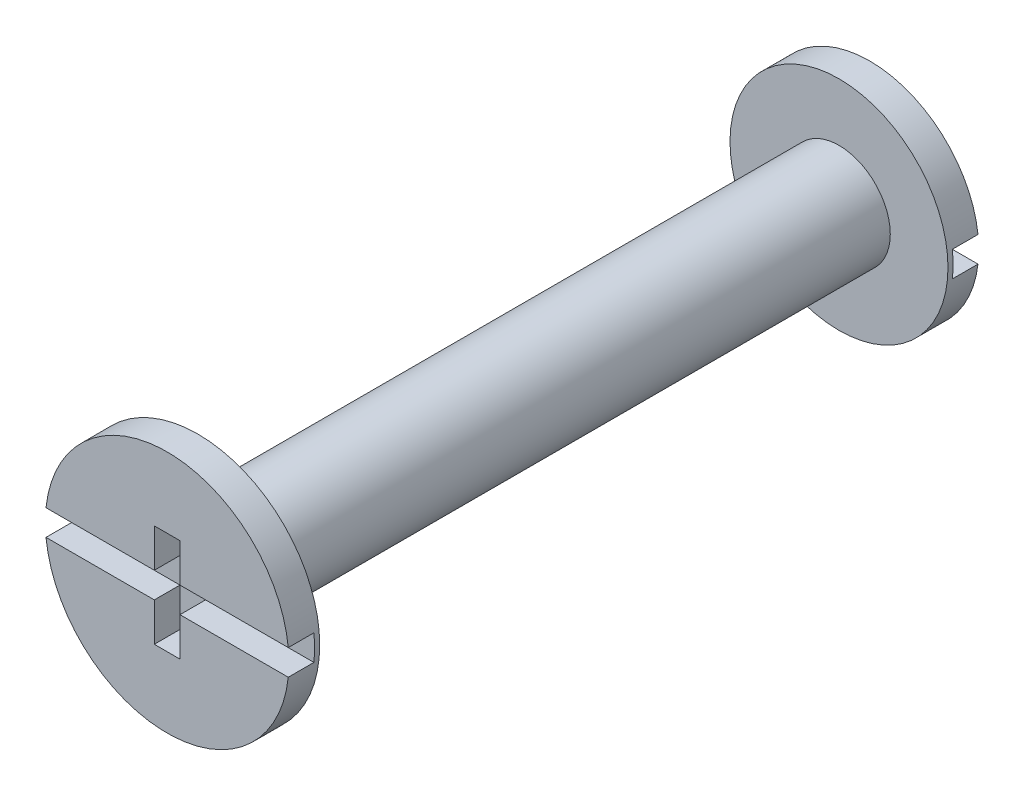
SolidWorks part; units mm, degrees
material "镀铬不锈钢"
ref_plane "前视基准面" through (0, 0, 0) normal (0, 0, 1) x (1, 0, 0)
ref_plane "上视基准面" through (0, 0, 0) normal (0, 1, 0) x (1, 0, 0)
ref_plane "右视基准面" through (0, 0, 0) normal (1, 0, 0) x (0, 0, -1)
sketch "草图1" plane through (0, 0, 0) normal (0, 0, 1) x (1, 0, 0)
  circle A0 centre (0, 0) radius 4.25
  dimension "D1" = 8.5
extrude "凸台-拉伸1" add sketch "草图1" along normal blind 1.2
sketch "草图2" plane through (0, 0, 1.2) normal (0, 0, 1) x (1, 0, 0)
  circle A0 centre (0, 0) radius 2
  dimension "D1" = 4
extrude "凸台-拉伸2" add sketch "草图2" along normal blind 25
sketch "草图3" plane through (0, 0, 26.2) normal (0, 0, 1) x (1, 0, 0)
  circle A0 centre (0, 0) radius 4.75
extrude "凸台-拉伸3" add sketch "草图3" along normal blind 1.2
sketch "草图4" plane through (0, 0, 27.4) normal (0, 0, 1) x (1, 0, 0)
  line L1 (0, -0.8601) -> (0, -2) construction
  line L2 (-0.5, 2) -> (-0.5, 0.5)
  line L3 (0.5, 2) -> (0.5, 0.5)
  line L4 (-4.7236, -0.5) -> (-0.5, -0.5)
  line L5 (-4.7236, 0.5) -> (-0.5, 0.5)
  line L8 (-0.5, 4.75) -> (-0.5, -4.75) construction
  line L9 (0.5, 4.75) -> (0.5, -4.75) construction
  line L10 (0, 4.75) -> (0, -4.75) construction
  line L13 (-0.5, 2) -> (0.5, 2)
  line L14 (-0.5, -2) -> (0.5, -2)
  line L17 (0.5, -0.5) -> (4.7236, -0.5)
  line L21 (0.5, 0.5) -> (4.7236, 0.5)
  line L23 (-0.5, -0.5) -> (-0.5, -2)
  line L24 (0.5, -0.5) -> (0.5, -2)
  arc A2 (-4.7236, 0.5) -> (-4.7236, -0.5) centre (0, 0) ccw
  arc A3 (4.7236, -0.5) -> (4.7236, 0.5) centre (0, 0) ccw
  dimension "D1" = 0.5
  dimension "D2" = 0.5
extrude "切除-拉伸1" cut sketch "草图4" against normal blind 1
sketch "草图5" plane through (0, 0, 0) normal (0, 0, -1) x (-1, 0, 0)
  line L0 (-4.25, 0) -> (4.25, 0) construction
  line L1 (-4.7236, -0.5) -> (4.7236, -0.5)
  line L2 (-4.7236, 0.5) -> (4.7236, 0.5)
  line L3 (-4.25, -0.5) -> (4.25, -0.5) construction
  line L4 (-4.25, 0.5) -> (4.25, 0.5) construction
  circle A0 centre (0, 0) radius 4.25 construction
  arc A1 (-4.7236, 0.5) -> (-4.7236, -0.5) centre (0, 0) ccw
  arc A2 (4.7236, -0.5) -> (4.7236, 0.5) centre (0, 0) ccw
  dimension "D1" = 0.5
  dimension "D2" = 0.5
extrude "切除-拉伸2" cut sketch "草图5" against normal blind 1
